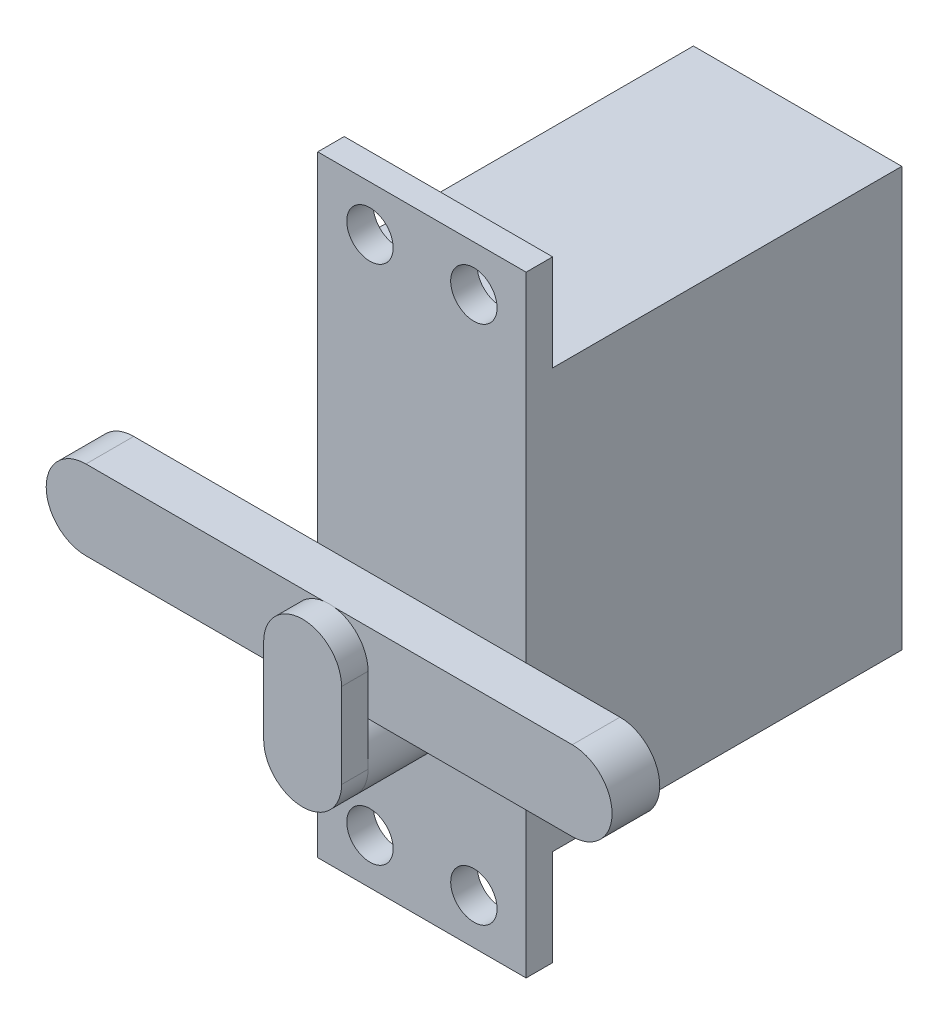
SolidWorks part; units mm, degrees
ref_plane "Front Plane" through (0, 0, 0) normal (0, 0, 1) x (1, 0, 0)
ref_plane "Top Plane" through (0, 0, 0) normal (0, 1, 0) x (1, 0, 0)
ref_plane "Right Plane" through (0, 0, 0) normal (1, 0, 0) x (0, 0, -1)
sketch "Sketch1" plane through (0, 0, 0) normal (1, 0, 0) x (0, 0, -1)
  line L0 (-54.9163, -3.1297) -> (-54.9163, 37.0023)
  line L1 (-54.9163, 37.0023) -> (-18.9245, 37.0023)
  line L2 (-18.9245, 37.0023) -> (-18.9245, -3.1297)
  line L3 (-54.9163, -3.1297) -> (-18.9245, -3.1297)
  dimension "D1" = 40.132
  dimension "D2" = 35.9918
extrude "Extrude1" add sketch "Sketch1" along normal mid plane 19.9644
sketch "Sketch2" plane through (0, 0, 54.9163) normal (0, 0, 1) x (1, 0, 0)
  line L0 (0, 37.0023) -> (0, -3.1297) construction
  line L1 (9.9822, 37.0023) -> (-9.9822, 37.0023) construction
  line L2 (9.9822, -3.1297) -> (-9.9822, -3.1297) construction
  line L3 (-9.9822, 6.2937) -> (9.9822, 6.2937) construction
  line L4 (-9.9822, 37.0023) -> (-9.9822, -3.1297) construction
  line L5 (9.9822, 37.0023) -> (9.9822, -3.1297) construction
  circle A0 centre (0, 6.2937) radius 3.7305
  dimension "D1" = 9.4234
extrude "Extrude2" add sketch "Sketch2" along normal blind 8.89 separate body
sketch "Sketch3" plane through (0, 0, 63.8063) normal (0, 0, 1) x (1, 0, 0)
  line L0 (23.2931, 10.488) -> (-23.2931, 10.488)
  line L1 (23.2931, 14.2994) -> (127.4796, -20.5835) construction
  line L2 (0, 10.488) -> (0, 27.5293) construction
  line L3 (23.2931, 18.1108) -> (-23.2931, 18.1108)
  arc A0 (23.2931, 10.488) -> (23.2931, 18.1108) centre (23.2931, 14.2994) ccw
  arc A1 (-23.2931, 10.488) -> (-23.2931, 18.1108) centre (-23.2931, 14.2994) cw
  point P7 (0, 18.1108)
extrude "Extrude3" add sketch "Sketch3" against normal blind 4.572 separate body
sketch "Sketch4" plane through (0, 0, 63.8063) normal (0, 0, 1) x (1, 0, 0)
  line L0 (-3.7305, 14.4241) -> (-3.7305, 6.2937)
  line L1 (3.7305, 14.4241) -> (3.7305, 6.2937)
  arc A0 (3.7305, 14.4241) -> (-3.7305, 14.4241) centre (0, 14.4241) ccw
  circle A1 centre (0, 6.2937) radius 3.7305
  arc A2 (-3.7305, 6.2937) -> (3.7305, 6.2937) centre (0, 6.2937) ccw
  dimension "D1" = 0
extrude "Extrude4" add sketch "Sketch4" along normal blind 2.54 separate body
sketch "Sketch5" plane through (0, 0, 54.9163) normal (0, 0, 1) x (1, 0, 0)
  line L0 (-9.9822, 37.0023) -> (-9.9822, -3.1297) construction
  line L1 (-9.9822, 37.0023) -> (9.9822, 37.0023)
  line L2 (-9.9822, 37.0023) -> (-9.9822, 46.2177)
  line L3 (-9.9822, 46.2177) -> (9.9822, 46.2177)
  line L4 (9.9822, 37.0023) -> (9.9822, 46.2177)
  line L5 (-9.9822, 16.9363) -> (18.6904, 16.9363) construction
  line L6 (0, 16.9363) -> (0, 47.5435) construction
  line L7 (-11.1656, 41.8645) -> (14.2027, 41.8645) construction
  line L8 (9.9822, -3.1297) -> (9.9822, -12.3451)
  line L9 (-9.9822, -12.3451) -> (9.9822, -12.3451)
  line L10 (-9.9822, -3.1297) -> (-9.9822, -12.3451)
  line L11 (-9.9822, -3.1297) -> (9.9822, -3.1297)
  circle A0 centre (4.9784, 41.8645) radius 2.2225
  circle A1 centre (-4.9784, 41.8645) radius 2.2225
  circle A2 centre (-4.9784, -7.9919) radius 2.2225
  circle A3 centre (4.9784, -7.9919) radius 2.2225
  dimension "D1" = 4.445
  dimension "D2" = 9.9568
  dimension "D3" = 4.9784
extrude "Extrude5" add sketch "Sketch5" against normal blind 2.54
